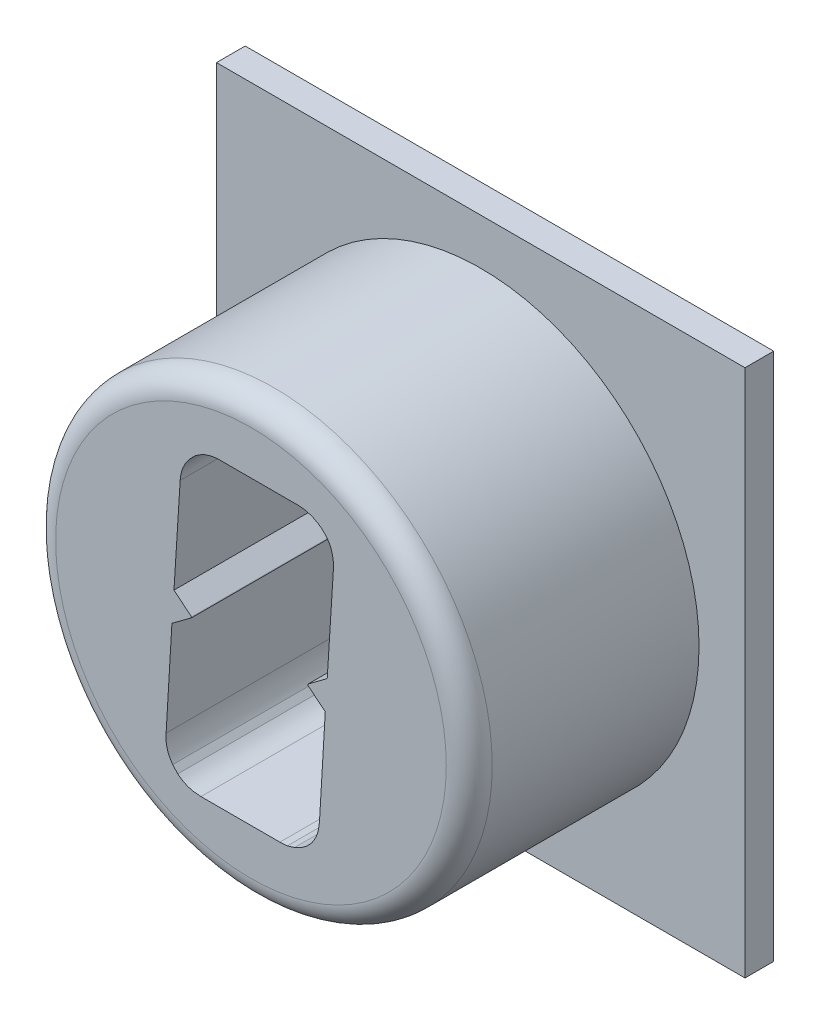
SolidWorks part; units mm, degrees
ref_plane "Спереди" through (0, 0, 0) normal (0, 0, 1) x (1, 0, 0)
ref_plane "Сверху" through (0, 0, 0) normal (0, 1, 0) x (1, 0, 0)
ref_plane "Справа" through (0, 0, 0) normal (1, 0, 0) x (0, 0, -1)
sketch "Эскиз1" plane through (0, 0, 0) normal (0, 0, 1) x (1, 0, 0)
  circle A0 centre (0, 0) radius 3.8
  dimension "D1" = 7.6
extrude "Бобышка-Вытянуть1" add sketch "Эскиз1" along normal blind 4
sketch "Эскиз2" plane through (0, 0, 0) normal (0, 0, -1) x (-1, 0, 0)
  line L1 (-4.6, 4.6) -> (4.6, 4.6)
  line L2 (-4.6, 4.6) -> (-4.6, -4.6)
  line L3 (-4.6, -4.6) -> (4.6, -4.6)
  line L4 (4.6, 4.6) -> (4.6, -4.6)
  circle A0 centre (0, 0) radius 3.8 construction
  dimension "D1" = 4.6
  dimension "D2" = 4.6
  dimension "D3" = 4.6
  dimension "D4" = 4.6
extrude "Бобышка-Вытянуть2" add sketch "Эскиз2" along normal blind 0.5
fillet "Скругление1" radius 0.4 1 edges at (3.8, 0, 4)
sketch "Эскиз3" plane through (0, 0, 4) normal (0, 0, 1) x (1, 0, 0)
  text T0 "8" font "7-Segment" height in points 20
extrude "Вырез-Вытянуть1" cut sketch "Эскиз3" against normal blind 4
sketch "Эскиз5" plane through (0, 0, 4) normal (0, 0, 1) x (1, 0, 0)
  line L0 (1.0802, 2.5835) -> (0.9604, 2.6245)
  line L1 (0.8327, 2.6374) -> (0.9604, 2.6245) construction
  line L2 (-0.5425, 2.6374) -> (0.8327, 2.6374) construction
  line L3 (0.8327, 2.6374) -> (0.9604, 2.6245)
  line L4 (-0.5425, 2.6374) -> (0.8327, 2.6374)
  line L5 (1.4355, 1.9828) -> (1.3277, 0.2772) construction
  line L6 (1.4355, 1.9828) -> (1.3277, 0.2772)
  line L7 (-0.9677, 2.4907) -> (-1.0615, 2.3949)
  line L8 (-1.3759, -0.2408) -> (-1.1443, -0.0691) construction
  line L9 (-1.1313, 0.1065) -> (-1.3399, 0.2772) construction
  line L10 (1.0852, -0.0691) -> (1.2938, -0.2398) construction
  line L11 (1.3277, 0.2772) -> (1.0992, 0.1065) construction
  line L12 (1.2938, -0.2398) -> (1.193, -1.9443) construction
  line L13 (-1.4767, -1.9463) -> (-1.3759, -0.2408) construction
  line L14 (-1.3399, 0.2772) -> (-1.2321, 1.9848) construction
  line L15 (-1.3759, -0.2408) -> (-1.1443, -0.0691)
  line L16 (-1.1313, 0.1065) -> (-1.3399, 0.2772)
  line L17 (1.0852, -0.0691) -> (1.2938, -0.2398)
  line L18 (1.3277, 0.2772) -> (1.0992, 0.1065)
  line L19 (1.2938, -0.2398) -> (1.193, -1.9443)
  line L20 (-1.4767, -1.9463) -> (-1.3759, -0.2408)
  line L21 (-1.3399, 0.2772) -> (-1.2321, 1.9848)
  line L22 (0.5034, -2.6) -> (-0.8699, -2.6) construction
  line L23 (0.5034, -2.6) -> (-0.8699, -2.6)
  line L24 (0.6311, -2.593) -> (0.5034, -2.6) construction
  line L25 (0.6311, -2.593) -> (0.5034, -2.6)
  line L26 (-1.3619, -2.3645) -> (-1.2741, -2.4603)
  line L27 (0.6311, -2.593) -> (0.7598, -2.5531)
  line L28 (1.0992, 0.1065) -> (0.9796, 0.0173)
  line L29 (0.9796, 0.0173) -> (1.0852, -0.0691)
  line L30 (-1.1313, 0.1065) -> (-1.0249, 0.0194)
  line L31 (-1.0249, 0.0194) -> (-1.1443, -0.0691)
  spline S0 degree 3 poles (-1962.094, 395.4122) (23.3967, -9.0402) (-2.1674, -0.7126) (-1.1844, 2.2045) (0.1548, 4.9412) (24.6397, -7.7161) (-1662.9344, 1114.9685) knots -19.554132 -19.554132 -19.554132 -19.554132 0.251768 0.497341 0.744977 20.326644 20.326644 20.326644 20.326644 only from (-1.2321, 1.9848) to (-1.0615, 2.3949) construction
  spline S1 degree 3 poles (-1018.6234, 1724.1502) (6.6515, -22.736) (-3.73, 1.3044) (-0.7678, 2.6033) (2.2537, 3.4048) (8.7851, -22.5564) (-254.4622, 1986.3754) knots -20.330991 -20.330991 -20.330991 -20.330991 0.255165 0.501082 0.748531 20.604003 20.604003 20.604003 20.604003 only from (-0.9677, 2.4907) to (-0.5425, 2.6374) construction
  spline S2 degree 3 poles (-1.2321, 1.9848) (-1.2282, 2.0226) (-1.2205, 2.0974) (-1.1844, 2.2045) (-1.1345, 2.3065) (-1.0861, 2.3652) (-1.0615, 2.3949) knots 0 0 0 0 0.251768 0.497341 0.744977 1 1 1 1
  spline S3 degree 3 poles (-0.9677, 2.4907) (-0.9357, 2.5132) (-0.873, 2.5572) (-0.7678, 2.6033) (-0.6572, 2.6327) (-0.581, 2.6358) (-0.5425, 2.6374) knots 0 0 0 0 0.255165 0.501082 0.748531 1 1 1 1
  spline S4 degree 3 poles (1001.1731, 1734.5376) (-15.6511, -14.7049) (-1.1692, 4.2661) (1.2433, 2.4843) (1.3072, 2.4209) (1.359, 2.3493) (1.3974, 2.2687) (1.4228, 2.1804) (1.8919, -0.8838) (-21.8121, -5.1174) (1999.306, 92.1906) knots -11.602951 -11.602951 -11.602951 -11.602951 0.133244 0.257459 0.376453 0.493208 0.61029 0.732843 0.861093 13.000634 13.000634 13.000634 13.000634 only from (1.0802, 2.5835) to (1.4355, 1.9828) construction
  spline S5 degree 3 poles (1.0802, 2.5835) (1.11, 2.5688) (1.1675, 2.5403) (1.2433, 2.4843) (1.3072, 2.4209) (1.359, 2.3493) (1.3974, 2.2687) (1.4228, 2.1804) (1.4375, 2.084) (1.4362, 2.0174) (1.4355, 1.9828) knots 0 0 0 0 0.133244 0.257459 0.376453 0.493208 0.61029 0.732843 0.861093 1 1 1 1
  spline S6 degree 3 poles (1982.2316, -276.0837) (-19.7493, 7.6083) (1.9564, 1.1339) (1.1588, -2.1466) (1.1216, -2.2358) (1.0732, -2.3171) (1.0124, -2.3897) (0.9399, -2.454) (-1.8372, -4.2685) (-15.3324, 14.4758) (919.232, -1779.0939) knots -12.347589 -12.347589 -12.347589 -12.347589 0.134544 0.260435 0.381865 0.499402 0.617479 0.738844 0.865338 13.126167 13.126167 13.126167 13.126167 only from (1.193, -1.9443) to (0.7598, -2.5531) construction
  spline S7 degree 3 poles (-239.4997, -1988.223) (8.2923, 21.8639) (1.9987, -3.3349) (-1.0896, -2.5683) (-3.7791, -1.3771) (7.5578, 22.4771) (-1058.6231, -1700.0114) knots -20.996403 -20.996403 -20.996403 -20.996403 0.261631 0.511336 0.755025 20.333958 20.333958 20.333958 20.333958 only from (-0.8699, -2.6) to (-1.2741, -2.4603) construction
  spline S8 degree 3 poles (-1759.7255, -955.2456) (25.1707, 5.7041) (-0.4873, -4.8772) (-1.4609, -2.1707) (-2.0188, 0.9035) (24.494, 5.4341) (-1998.8667, -103.0731) knots -18.557774 -18.557774 -18.557774 -18.557774 0.246767 0.489725 0.738833 21.261126 21.261126 21.261126 21.261126 only from (-1.3619, -2.3645) to (-1.4767, -1.9463) construction
  spline S9 degree 3 poles (1.193, -1.9443) (1.1895, -1.9797) (1.1828, -2.0482) (1.1588, -2.1466) (1.1216, -2.2358) (1.0732, -2.3171) (1.0124, -2.3897) (0.9399, -2.454) (0.8549, -2.5095) (0.7922, -2.5383) (0.7598, -2.5531) knots 0 0 0 0 0.134544 0.260435 0.381865 0.499402 0.617479 0.738844 0.865338 1 1 1 1
  spline S10 degree 3 poles (-0.8699, -2.6) (-0.908, -2.5983) (-0.9824, -2.5949) (-1.0896, -2.5683) (-1.1885, -2.5245) (-1.2455, -2.4817) (-1.2741, -2.4603) knots 0 0 0 0 0.261631 0.511336 0.755025 1 1 1 1
  spline S11 degree 3 poles (-1.3619, -2.3645) (-1.3826, -2.3343) (-1.4236, -2.2744) (-1.4609, -2.1707) (-1.4809, -2.0605) (-1.4781, -1.985) (-1.4767, -1.9463) knots 0 0 0 0 0.246767 0.489725 0.738833 1 1 1 1
extrude "Вырез-Вытянуть2" cut sketch "Эскиз5" against normal blind 4
sketch "Эскиз6" plane through (0, 0, 0) normal (0, 0, 1) x (1, 0, 0)
  circle A0 centre (0, 0) radius 0.6
  dimension "D1" = 1.2
extrude "Вырез-Вытянуть3" cut sketch "Эскиз6" against normal through all
